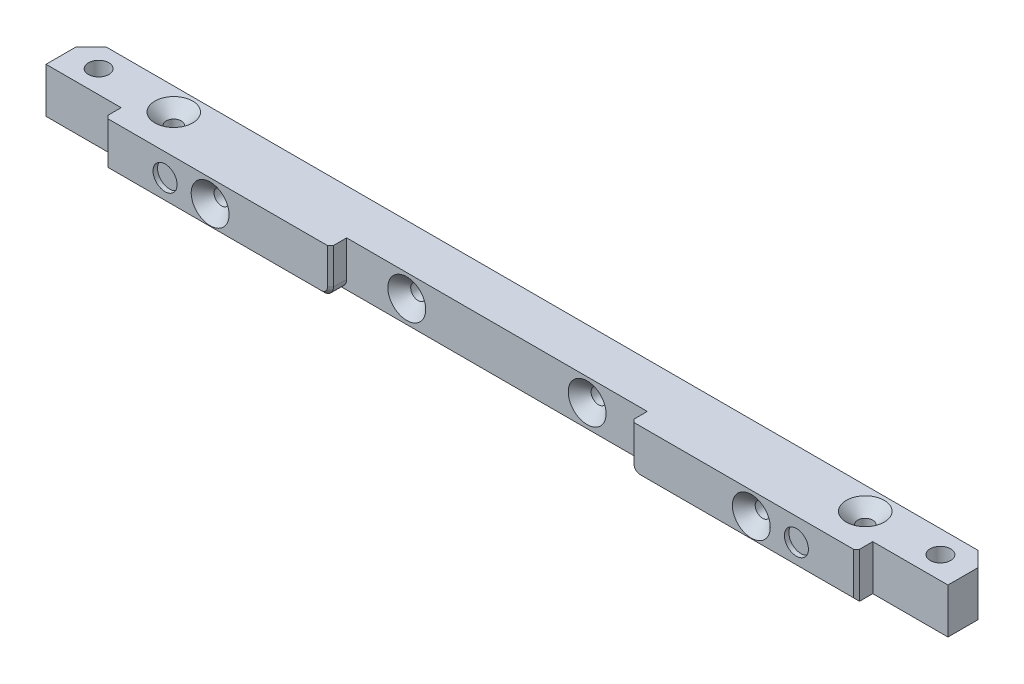
SolidWorks part; units mm, degrees
material "3.1355 (EN-AW 2024)"
ref_plane "Front" through (0, 0, 0) normal (0, 0, 1) x (1, 0, 0)
ref_plane "Top" through (0, 0, 0) normal (0, 1, 0) x (1, 0, 0)
ref_plane "Right" through (0, 0, 0) normal (1, 0, 0) x (0, 0, -1)
sketch "Эскиз1" plane through (0, 0, 0) normal (0, 1, 0) x (1, 0, 0)
  line L1 (-150, 7.5) -> (150, 7.5)
  line L2 (-150, 7.5) -> (-150, -7.5)
  line L3 (-150, -7.5) -> (150, -7.5)
  line L4 (150, 7.5) -> (150, -7.5)
  line L5 (-150, 7.5) -> (150, -7.5) construction
  line L6 (-150, -7.5) -> (150, 7.5) construction
  point P0 (0, 0)
  dimension "D1" = 300
  dimension "D2" = 15
extrude "База" add sketch "Эскиз1" along normal blind 15
hole_wizard "Крепление шарнира M6" positions "Эскиз2" profile "Эскиз3" tap size "M6" standard "DIN" end condition through all
sketch "Эскиз2" plane through (0, 15, 0) normal (0, 1, 0) x (1, 0, 0)
  line L6 (-115, 0) -> (0, 0) construction
  line L7 (0, 0) -> (115, 0) construction
  point P3 (-115, 0)
  point P5 (115, 0)
  dimension "D1" = 230
sketch "Эскиз3" plane through (-115, 15, 0) normal (1, 0, 0) x (0, 0, 1)
  line L0 (0, 0) -> (0, 15)
  line L1 (0, 15) -> (2.5, 15)
  line L2 (2.5, 15) -> (2.5, 3.8)
  line L3 (2.5, 3.8) -> (6.3, 0)
  line L5 (6.3, 0) -> (0, 0)
  line L6 (-2.5, 3.8) -> (-6.3, 0) construction
  line L11 (0, -6.35) -> (0, 107.95) construction
  dimension "Диаметр проходного сверла" = 5
  dimension "Глубина проходного сверла" = 15
  dimension "Диаметр передней зенковки" = 12.6
  dimension "Угол передней зенковки" = 90
cosmetic thread "Отверстие резьбы12" parameters "D2"=6
cosmetic thread "Отверстие резьбы13" parameters "D2"=6
hole_wizard "Шпилька-M8" positions "Эскиз6" profile "Эскиз7" tap size "M8" standard "DIN" end condition through all
sketch "Эскиз6" plane through (0, 15, 0) normal (0, 1, 0) x (1, 0, 0)
  line L2 (-140, 0) -> (-150, 0) construction
  line L3 (-150, 7.5) -> (-150, -7.5) construction
  line L8 (140, 0) -> (150, 0) construction
  line L9 (150, -7.5) -> (150, 7.5) construction
  point P0 (-140, 0)
  point P2 (140, 0)
  dimension "D1" = 10
cosmetic thread "Отверстие резьбы1" parameters "D2"=8
cosmetic thread "Отверстие резьбы2" parameters "D2"=8
sketch "Эскиз7" plane through (-140, 15, 0) normal (1, 0, 0) x (0, 0, 1)
  line L0 (0, 0) -> (0, 15)
  line L1 (0, 15) -> (3.4, 15)
  line L2 (3.4, 15) -> (3.4, 0)
  line L5 (3.4, 0) -> (0, 0)
  line L11 (0, -6.35) -> (0, 107.95) construction
  dimension "Диаметр проходного сверла" = 6.8
  dimension "Глубина проходного сверла" = 15
sketch "Эскиз8" plane through (0, 0, 7.5) normal (0, 0, 1) x (1, 0, 0)
  line L0 (-150, 15) -> (150, 15) construction
  line L1 (-125, 15) -> (125, 15)
  line L2 (-125, 15) -> (-125, 0)
  line L3 (-125, 0) -> (125, 0)
  line L4 (125, 15) -> (125, 0)
  line L5 (-150, 0) -> (150, 0) construction
  point P8 (0, 0)
  dimension "D1" = 250
extrude "Направляющая" add sketch "Эскиз8" along normal blind 5.4
sketch "Эскиз9" plane through (0, 0, 12.9) normal (0, 0, 1) x (1, 0, 0)
  line L0 (0, 7.5) -> (0, 15) construction
  line L1 (125, 15) -> (-125, 15) construction
  line L2 (0, 7.5) -> (0, 0) construction
  line L5 (-105, 7.5) -> (105, 7.5) construction
  circle A1 centre (-105, 7.5) radius 4
  circle A2 centre (105, 7.5) radius 4
  point P1 (0, 7.5)
  dimension "D1" = 8
  dimension "D2" = 210
extrude "Магниты" cut sketch "Эскиз9" against normal blind 1.5
sketch "Эскиз10" plane through (0, 0, 12.9) normal (0, 0, 1) x (1, 0, 0)
  line L0 (125, 15) -> (-125, 15) construction
  line L1 (-50, 15) -> (50, 15)
  line L2 (-50, 15) -> (-50, 0)
  line L3 (-50, 0) -> (50, 0)
  line L4 (50, 15) -> (50, 0)
  line L5 (-125, 0) -> (125, 0) construction
  point P8 (0, 15)
  dimension "D1" = 100
extrude "Вырез" cut sketch "Эскиз10" against normal blind 5.4
hole_wizard "Прижим-1-M6" positions "Эскиз4" profile "Эскиз5" tap size "M6" standard "DIN" end condition through all
sketch "Эскиз4" plane through (0, 0, 12.9) normal (0, 0, 1) x (1, 0, 0)
  line L23 (90, 7.5) -> (30, 7.5) construction
  line L24 (30, 7.5) -> (-30, 7.5) construction
  line L25 (-30, 7.5) -> (-90, 7.5) construction
  line L26 (0, 7.5) -> (0, 15) construction
  line L27 (150, 15) -> (-150, 15) construction
  line L30 (0, 7.5) -> (0, 0) construction
  point P4 (-90, 7.5)
  point P8 (90, 7.5)
  point P65 (0, 7.5)
  dimension "D1" = 180
sketch "Эскиз5" plane through (-90, 7.5, 12.9) normal (1, 0, 0) x (0, -1, 0)
  line L0 (0, 0) -> (0, 20.4)
  line L1 (0, 20.4) -> (2.5, 20.4)
  line L2 (2.5, 20.4) -> (2.5, 3.8)
  line L3 (2.5, 3.8) -> (6.3, 0)
  line L5 (6.3, 0) -> (0, 0)
  line L6 (-2.5, 3.8) -> (-6.3, 0) construction
  line L11 (0, -6.35) -> (0, 107.95) construction
  dimension "Диаметр проходного сверла" = 5
  dimension "Глубина проходного сверла" = 20.4
  dimension "Диаметр передней зенковки" = 12.6
  dimension "Угол передней зенковки" = 90
cosmetic thread "Отверстие резьбы16" parameters "D2"=6
cosmetic thread "Отверстие резьбы17" parameters "D2"=6
hole_wizard "Прижим-2-M6" positions "Эскиз11" profile "Эскиз12" tap size "M6" standard "ISO" end condition through all
sketch "Эскиз11" plane through (0, 0, 7.5) normal (0, 0, 1) x (1, 0, 0)
  line L0 (-30, 7.5) -> (0, 7.5) construction
  line L1 (0, 7.5) -> (30, 7.5) construction
  line L4 (0, 7.5) -> (0, 15) construction
  line L5 (50, 15) -> (-50, 15) construction
  line L8 (0, 7.5) -> (0, 0) construction
  point P0 (-30, 7.5)
  point P2 (30, 7.5)
  dimension "D1" = 60
sketch "Эскиз12" plane through (-30, 7.5, 7.5) normal (1, 0, 0) x (0, -1, 0)
  line L0 (0, 0) -> (0, 15)
  line L1 (0, 15) -> (2.5, 15)
  line L2 (2.5, 15) -> (2.5, 3.8)
  line L3 (2.5, 3.8) -> (6.3, 0)
  line L5 (6.3, 0) -> (0, 0)
  line L6 (-2.5, 3.8) -> (-6.3, 0) construction
  line L11 (0, -6.35) -> (0, 107.95) construction
  dimension "Диаметр проходного сверла" = 5
  dimension "Глубина проходного сверла" = 15
  dimension "Диаметр передней зенковки" = 12.6
  dimension "Угол передней зенковки" = 90
cosmetic thread "Отверстие резьбы20" parameters "D1"=0, "D2"=6
cosmetic thread "Отверстие резьбы21" parameters "D1"=0, "D2"=6
fillet "Скругление1" radius 3 2 edges at (50, 0, 10.2) (-50, 0, 10.2)
chamfer "Фаска1" distance 5 angle 45 2 edges at (150, 7.5, -7.5) (-150, 7.5, -7.5)
chamfer "Фаска2" distance 1 angle 45 8 edges at (125, 7.5, 12.9) (89, 0, 12.9) (50.8787, 0.8787, 12.9) (50, 9, 12.9) (-89, 0, 12.9) (-50.8787, 0.8787, 12.9) (-50, 9, 12.9) (-125, 7.5, 12.9)
